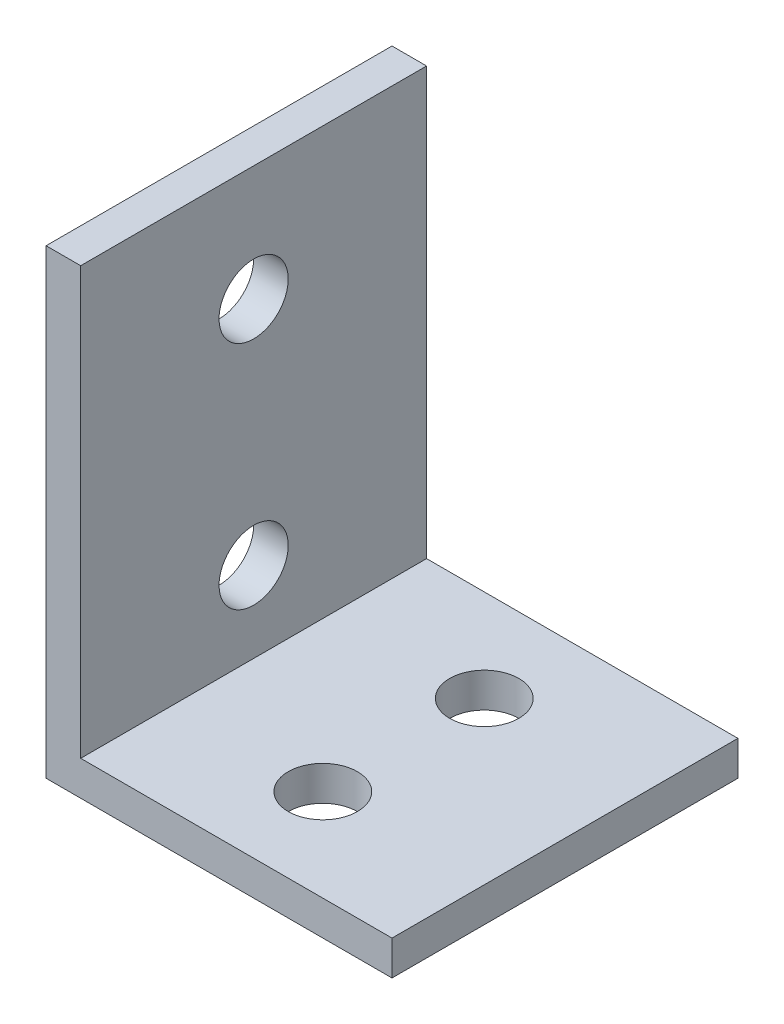
SolidWorks part; units mm, degrees
ref_plane "Plan de face" through (0, 0, 0) normal (0, 0, 1) x (1, 0, 0)
ref_plane "Plan de dessus" through (0, 0, 0) normal (0, 1, 0) x (1, 0, 0)
ref_plane "Plan de droite" through (0, 0, 0) normal (1, 0, 0) x (0, 0, -1)
sketch "Esquisse1" plane through (0, 0, 0) normal (0, 0, 1) x (1, 0, 0)
  line L0 (-28.5676, 0.0008) -> (-28.5676, -19.9992)
  line L1 (-28.5676, -19.9992) -> (-13.5676, -19.9992)
  line L2 (-13.5676, -19.9992) -> (-13.5676, -18.4992)
  line L3 (-13.5676, -18.4992) -> (-27.0676, -18.4992)
  line L4 (-27.0676, -18.4992) -> (-27.0676, 0.0008)
  line L5 (-27.0676, 0.0008) -> (-28.5676, 0.0008)
  dimension "D1" = 1.5
  dimension "D2" = 1.5
  dimension "D3" = 15
  dimension "D4" = 20
extrude "Extrusion1" add sketch "Esquisse1" along normal blind 15
sketch "Esquisse2" plane through (0, -18.4992, 0) normal (0, 1, 0) x (-1, 0, 0)
  line L0 (20.5676, 4) -> (20.5676, 11) construction
  line L1 (13.5676, 15) -> (13.5676, 0) construction
  line L3 (13.5676, 0) -> (27.0676, 0) construction
  circle A0 centre (20.5676, 4) radius 1.5
  circle A1 centre (20.5676, 11) radius 1.5
  point P4 (13.5676, 7.5)
  dimension "D1" = 7
  dimension "D2" = 7
  dimension "D3" = 4
extrude "Extrusion2" cut sketch "Esquisse2" against normal blind 15
sketch "Esquisse3" plane through (-27.0676, 0, 0) normal (1, 0, 0) x (0, 0, -1)
  line L0 (-7.5, -4.9992) -> (-7.5, -14.9992) construction
  line L1 (-15, 0.0008) -> (0, 0.0008) construction
  line L2 (0, -18.4992) -> (0, 0.0008) construction
  circle A0 centre (-7.5, -4.9992) radius 1.5
  circle A1 centre (-7.5, -14.9992) radius 1.5
  dimension "D1" = 10
  dimension "D3" = 7.5
  dimension "D2" = 5
extrude "Extrusion3" cut sketch "Esquisse3" against normal blind 15
